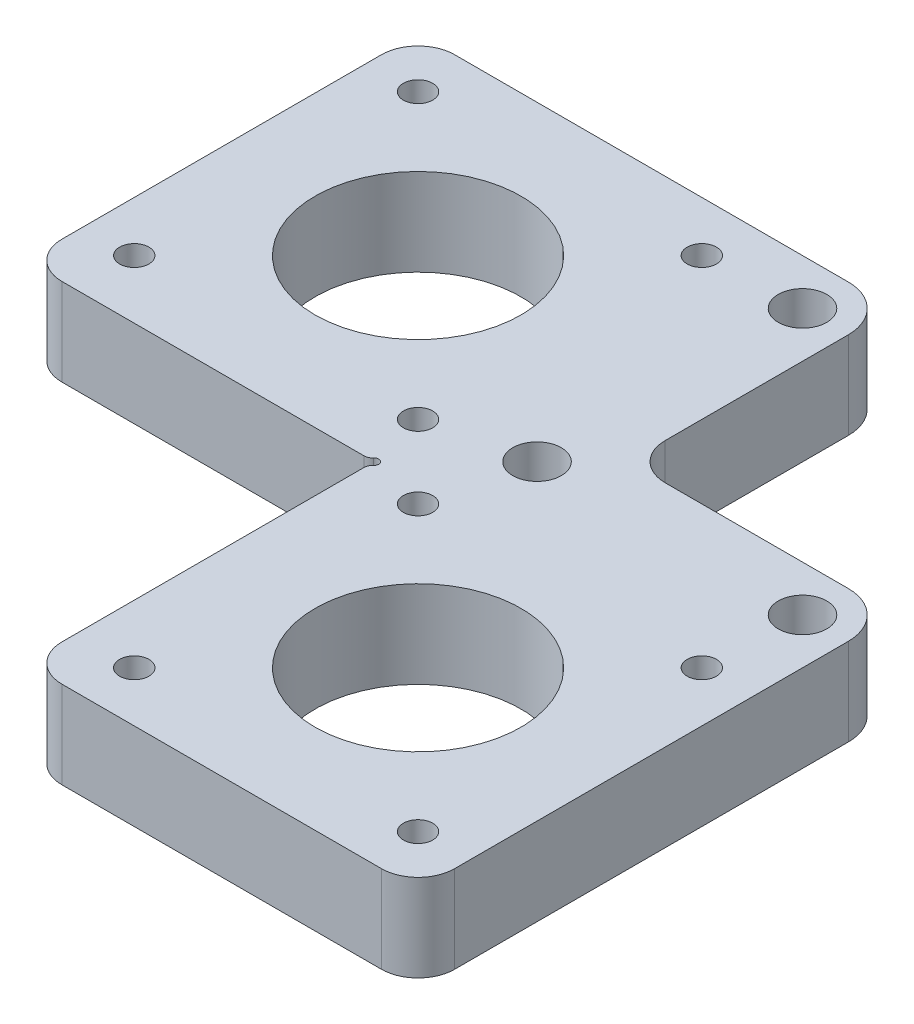
SolidWorks part; units mm, degrees
material "AISI 1045 Steel, cold drawn"
ref_plane "Front Plane" through (0, 0, 0) normal (0, 0, 1) x (1, 0, 0)
ref_plane "Top Plane" through (0, 0, 0) normal (0, 1, 0) x (1, 0, 0)
ref_plane "Right Plane" through (0, 0, 0) normal (1, 0, 0) x (0, 0, -1)
sketch "Sketch1" plane through (0, 0, 0) normal (0, 1, 0) x (1, 0, 0)
  line L1 (60, -21) -> (18, -21) construction
  line L2 (60, -21) -> (60, 21) construction
  line L3 (60, 21) -> (18, 21) construction
  line L4 (18, -21) -> (18, 21) construction
  line L5 (60, -21) -> (18, 21) construction
  line L6 (60, 21) -> (18, -21) construction
  line L7 (21, 18) -> (-21, 18) construction
  line L8 (21, 18) -> (21, 60) construction
  line L9 (21, 60) -> (-21, 60) construction
  line L10 (-21, 18) -> (-21, 60) construction
  line L11 (21, 18) -> (-21, 60) construction
  line L12 (21, 60) -> (-21, 18) construction
  line L14 (60, -21) -> (60, 31)
  line L15 (60, 31) -> (31, 31)
  line L16 (31, 31) -> (31, 60)
  line L17 (31, 60) -> (-21, 60)
  line L18 (-21, 60) -> (-21, 18)
  line L19 (-21, 18) -> (18, 18)
  line L20 (18, 18) -> (18, -21)
  line L21 (18, -21) -> (60, -21)
  point P0 (39, 0)
  point P5 (0, 39)
  dimension "D1" = 42
  dimension "D2" = 39
  dimension "D3" = 39
  dimension "D4" = 10
  dimension "D5" = 10
extrude "Boss-Extrude1" add sketch "Sketch1" along normal blind 9.525
hole_wizard "Ø22.5 (22.5) Diameter Hole1" positions "Sketch5" profile "Sketch7" hole size "Ø22.5" standard "ANSI Metric" end condition through all
sketch "Sketch5" plane through (0, 9.525, 0) normal (0, 1, 0) x (1, 0, 0)
  point P0 (0, 39)
  point P3 (39, 0)
sketch "Sketch7" plane through (0, 9.525, -39) normal (1, 0, 0) x (0, 0, 1)
  line L0 (0, 0) -> (0, 9.525)
  line L1 (0, 9.525) -> (11.25, 9.525)
  line L2 (11.25, 9.525) -> (11.25, 0)
  line L5 (11.25, 0) -> (0, 0)
  line L11 (0, -6.35) -> (0, 107.95) construction
  dimension "Thru Hole Dia." = 22.5
  dimension "Thru Hole Depth" = 9.525
sketch "Sketch8" plane through (0, 0, 0) normal (0, 1, 0) x (1, 0, 0)
  line L0 (21, 60) -> (-21, 18) construction
  line L1 (15.5, 23.5) -> (-15.5, 23.5)
  line L2 (15.5, 23.5) -> (15.5, 54.5)
  line L3 (15.5, 54.5) -> (-15.5, 54.5)
  line L4 (-15.5, 23.5) -> (-15.5, 54.5)
  line L5 (15.5, 23.5) -> (-15.5, 54.5) construction
  line L6 (15.5, 54.5) -> (-15.5, 23.5) construction
  line L7 (21, 18) -> (-21, 60) construction
  line L8 (60, 21) -> (18, -21) construction
  line L9 (23.5, -15.5) -> (54.5, -15.5)
  line L10 (23.5, -15.5) -> (23.5, 15.5)
  line L11 (23.5, 15.5) -> (54.5, 15.5)
  line L12 (54.5, -15.5) -> (54.5, 15.5)
  line L13 (23.5, -15.5) -> (54.5, 15.5) construction
  line L14 (23.5, 15.5) -> (54.5, -15.5) construction
  point P0 (0, 39)
  point P9 (39, 0)
  dimension "D1" = 31
hole_wizard "M3 Clearance Hole1" positions "Sketch9" profile "Sketch10" hole size "M3" standard "ANSI Metric" end condition through all
sketch "Sketch9" plane through (0, 0, 0) normal (0, -1, 0) x (-1, 0, 0)
  point P0 (-54.5, 15.5)
  point P3 (-23.5, 15.5)
  point P6 (-23.5, -15.5)
  point P9 (-54.5, -15.5)
  point P12 (-15.5, 54.5)
  point P15 (-15.5, 23.5)
  point P18 (15.5, 23.5)
  point P21 (15.5, 54.5)
sketch "Sketch10" plane through (54.5, 0, -15.5) normal (1, 0, 0) x (0, 0, -1)
  line L0 (0, 0) -> (0, 9.525)
  line L1 (0, 9.525) -> (1.6, 9.525)
  line L2 (1.6, 9.525) -> (1.6, 0)
  line L5 (1.6, 0) -> (0, 0)
  line L11 (0, -6.35) -> (0, 107.95) construction
  dimension "Thru Hole Dia." = 3.2
  dimension "Thru Hole Depth" = 9.525
hole_wizard "M5 Clearance Hole1" positions "Sketch11" profile "Sketch12" hole size "M5" standard "ANSI Metric" end condition through all
sketch "Sketch11" plane through (0, 9.525, 0) normal (0, 1, 0) x (1, 0, 0)
  line L0 (55, 26) -> (26, 26) construction
  line L1 (26, 26) -> (26, 55) construction
  line L3 (31, 31) -> (31, 60) construction
  line L4 (31, 60) -> (-21, 60) construction
  line L5 (60, -21) -> (60, 31) construction
  line L6 (60, 31) -> (31, 31) construction
  point P0 (26, 55)
  point P2 (26, 26)
  point P4 (55, 26)
  dimension "D1" = 5
  dimension "D2" = 5
  dimension "D3" = 5
  dimension "D4" = 5
sketch "Sketch12" plane through (26, 9.525, -55) normal (1, 0, 0) x (0, 0, 1)
  line L0 (0, 0) -> (0, 9.525)
  line L1 (0, 9.525) -> (2.65, 9.525)
  line L2 (2.65, 9.525) -> (2.65, 0)
  line L5 (2.65, 0) -> (0, 0)
  line L11 (0, -6.35) -> (0, 107.95) construction
  dimension "Thru Hole Dia." = 5.3
  dimension "Thru Hole Depth" = 9.525
ref_plane "Plane1" through (0, 0, 0) normal (0.7071, 0, 0.7071) x (0.7071, 0, -0.7071)
sketch "Sketch16" plane through (0, 9.525, 0) normal (0, 1, 0) x (1, 0, 0)
  line L1 (17.1, 17.1) -> (-21, 17.1)
  line L2 (17.1, 17.1) -> (17.1, -21)
  line L6 (-21, 17.1) -> (-21, 18)
  line L7 (-21, 18) -> (18, 18)
  line L8 (18, 18) -> (18, -21)
  line L9 (18, -21) -> (17.1, -21)
  circle A0 centre (39, 0) radius 11.25 construction
  dimension "D1" = 21.9
extrude "Boss-Extrude2" add sketch "Sketch16" against normal up to surface (9.525 mm away) up to face at (26, 0, -52.35)
sketch "Sketch17" plane through (0, 9.525, 0) normal (0, 1, 0) x (1, 0, 0)
  circle A0 centre (17.1, 17.1) radius 0.5
  dimension "D1" = 1
extrude "Cut-Extrude1" cut sketch "Sketch17" against normal up to surface (9.525 mm away) up to face at (26, 0, -52.35)
fillet "Fillet2" radius 4 5 edges at (-21, 4.7625, -60) (31, 4.7625, -31) (60, 4.7625, 21) (17.1, 4.7625, 21) (-21, 4.7625, -17.1)
fillet "Fillet3" radius 5 2 edges at (60, 4.7625, -31) (31, 4.7625, -60)
fillet "Fillet4" radius 1 2 edges at (16.6, 4.7625, -17.1) (17.1, 4.7625, -16.6)
